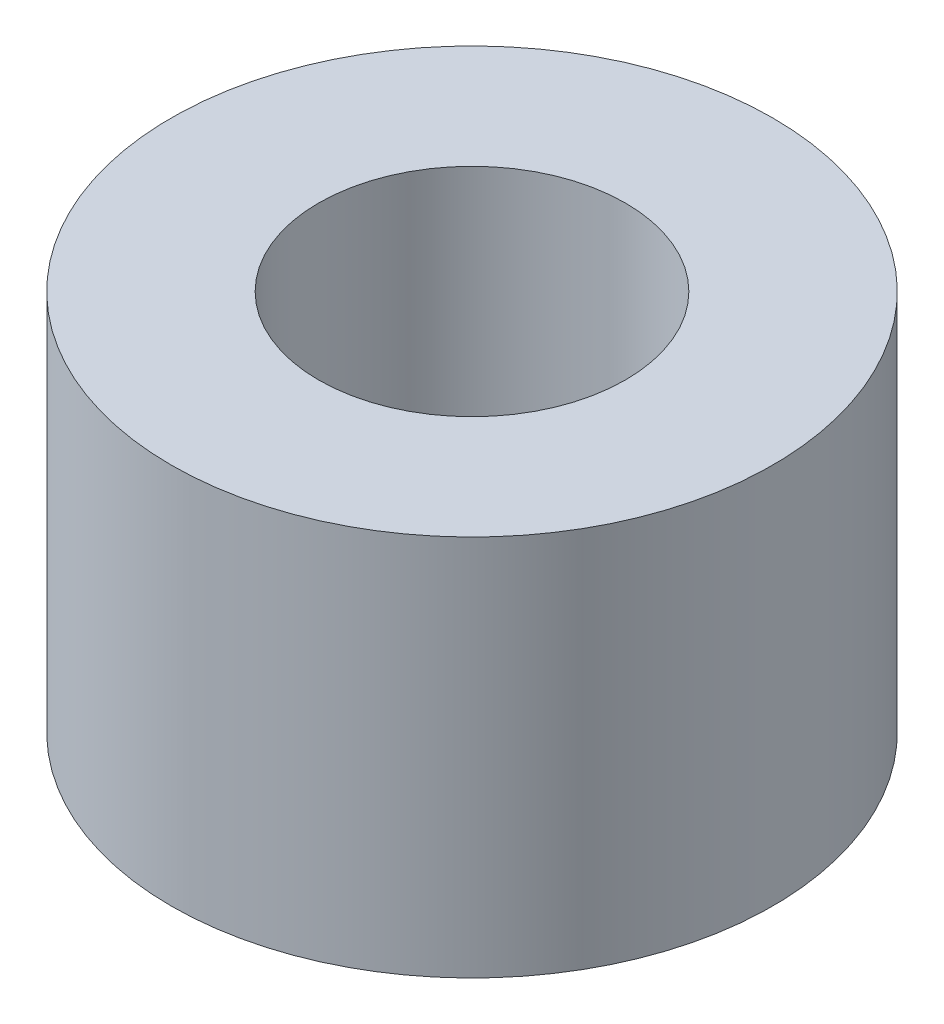
SolidWorks part; units mm, degrees
material "1060 Alloy"
ref_plane "Front Plane" through (0, 0, 0) normal (0, 0, 1) x (1, 0, 0)
ref_plane "Top Plane" through (0, 0, 0) normal (0, 1, 0) x (1, 0, 0)
ref_plane "Right Plane" through (0, 0, 0) normal (1, 0, 0) x (0, 0, -1)
sketch "Sketch1" plane through (0, 0, 0) normal (0, 1, 0) x (1, 0, 0)
  circle A0 centre (0, 0) radius 5
  circle A1 centre (0, 0) radius 2.55
  dimension "D1" = 5.1
  dimension "D2" = 10
extrude "Boss-Extrude1" add sketch "Sketch1" along normal blind 6.35
